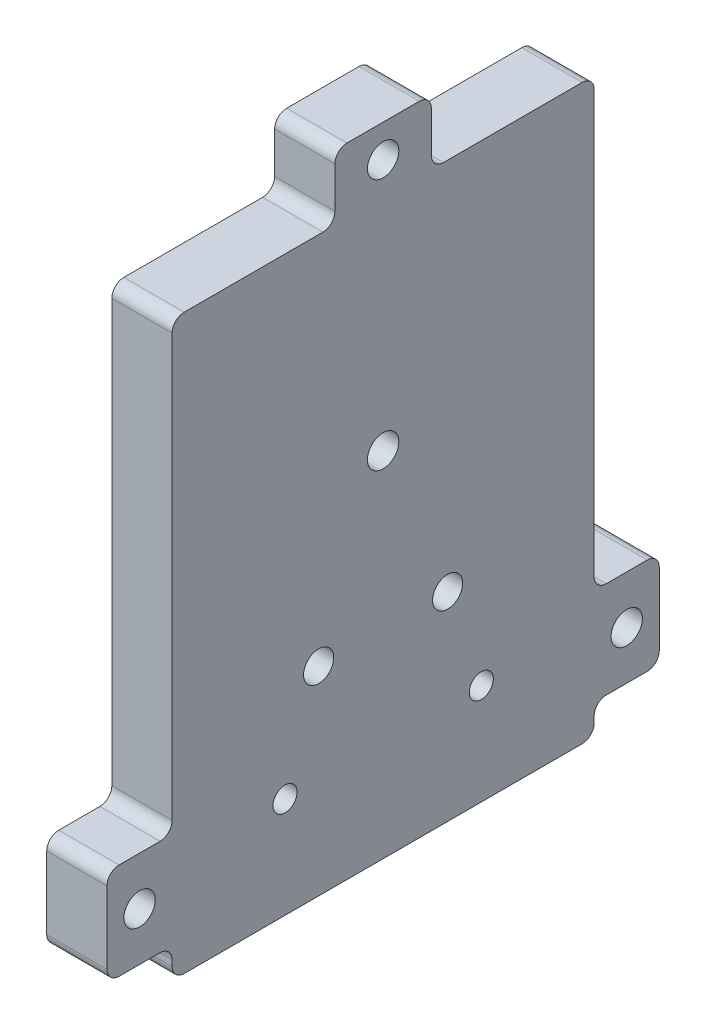
SolidWorks part; units mm, degrees
ref_plane "Front Plane" through (0, 0, 0) normal (0, 0, 1) x (1, 0, 0)
ref_plane "Top Plane" through (0, 0, 0) normal (0, 1, 0) x (1, 0, 0)
ref_plane "Right Plane" through (0, 0, 0) normal (1, 0, 0) x (0, 0, -1)
sketch "Sketch11" plane through (0, 0, 0) normal (1, 0, 0) x (0, 0, -1)
  line L0 (0, 0) -> (0, 16.256) construction
  line L1 (0, 0) -> (6.7945, 0) construction
  line L2 (0, 0) -> (10.3363, -10.3363) construction
  line L3 (0, -17.78) -> (0, 36.195) construction
  line L4 (-19.05, 36.195) -> (19.05, 36.195)
  line L5 (-19.05, 36.195) -> (-19.05, -17.78)
  line L6 (-19.05, -17.78) -> (19.05, -17.78)
  line L7 (19.05, 36.195) -> (19.05, -17.78)
  circle A5 centre (0, 16.256) radius 1.651
  circle A6 centre (6.7945, 0) radius 1.5875
  circle A7 centre (10.3363, -10.3363) radius 1.27
  circle A10 centre (-10.3363, -10.3363) radius 1.27
  circle A11 centre (-6.7945, 0) radius 1.5875
  dimension "D1" = 3.302
  dimension "D2" = 3.175
  dimension "D3" = 53.975
  dimension "D4" = 38.1
  dimension "D5" = 2.54
  dimension "D6" = 16.256
  dimension "D7" = 6.7945
  dimension "D8" = 10.3363
  dimension "D9" = 10.3363
  dimension "D10" = 17.78
extrude "Boss-Extrude1" add sketch "Sketch11" against normal blind 3.175
sketch "Sketch12" plane through (0, 0, 0) normal (1, 0, 0) x (0, 0, -1)
  line L0 (-22.225, 39.37) -> (-22.225, -20.955)
  line L1 (-22.225, -20.955) -> (22.225, -20.955)
  line L2 (22.225, -20.955) -> (22.225, 39.37)
  line L3 (22.225, 39.37) -> (-22.225, 39.37)
  line L4 (-19.05, 36.195) -> (-19.05, -17.78)
  line L5 (-19.05, -17.78) -> (19.05, -17.78)
  line L6 (19.05, -17.78) -> (19.05, 36.195)
  line L7 (19.05, 36.195) -> (-19.05, 36.195)
  line L8 (-19.05, 36.195) -> (-19.05, -17.78)
  line L9 (-19.05, -17.78) -> (19.05, -17.78)
  line L10 (19.05, -17.78) -> (19.05, 36.195)
  line L11 (19.05, 36.195) -> (-19.05, 36.195)
  dimension "D1" = 0
  dimension "D2" = 3.175
extrude "Boss-Extrude2" add sketch "Sketch12" against normal blind 6.35
sketch "Sketch13" plane through (0, 0, 0) normal (1, 0, 0) x (0, 0, -1)
  line L0 (22.225, 39.37) -> (-22.225, 39.37) construction
  line L1 (-22.225, -17.78) -> (-29.083, -17.78)
  line L2 (-22.225, -17.78) -> (-22.225, -7.62)
  line L3 (-22.225, -7.62) -> (-29.083, -7.62)
  line L4 (-29.083, -17.78) -> (-29.083, -7.62)
  line L5 (5.08, 39.37) -> (-5.08, 39.37)
  line L6 (5.08, 39.37) -> (5.08, 46.228)
  line L7 (5.08, 46.228) -> (-5.08, 46.228)
  line L8 (-5.08, 39.37) -> (-5.08, 46.228)
  line L9 (0, -20.955) -> (0, 39.37) construction
  line L10 (-22.225, -20.955) -> (22.225, -20.955) construction
  line L11 (-25.654, -17.78) -> (-25.654, -7.62) construction
  line L12 (-29.083, -12.7) -> (-22.225, -12.7) construction
  line L13 (-5.08, 42.799) -> (5.08, 42.799) construction
  line L14 (0, 46.228) -> (0, 39.37) construction
  line L15 (22.225, -7.62) -> (29.083, -7.62)
  line L16 (29.083, -17.78) -> (29.083, -7.62)
  line L17 (22.225, -17.78) -> (29.083, -17.78)
  line L18 (22.225, -17.78) -> (22.225, -7.62)
  line L19 (-19.05, -17.78) -> (19.05, -17.78) construction
  circle A0 centre (-25.654, -12.7) radius 1.651
  circle A1 centre (0, 42.799) radius 1.651
  circle A2 centre (25.654, -12.7) radius 1.651
  dimension "D5" = 3.302
  dimension "D6" = 3.302
  dimension "D1" = 10.16
  dimension "D2" = 6.858
  dimension "D3" = 10.16
  dimension "D4" = 6.858
extrude "Boss-Extrude3" add sketch "Sketch13" against normal up to surface (6.35 mm away) up to face at (-6.35, 9.2075, 0)
sketch "Sketch14" plane through (-3.175, 0, 0) normal (-1, 0, 0) x (0, 0, 1)
  circle A0 centre (-6.7945, 0) radius 1.5875 construction
  circle A1 centre (-6.7945, 0) radius 1.5875
  circle A2 centre (6.7945, 0) radius 1.5875 construction
  circle A3 centre (6.7945, 0) radius 1.5875
  circle A4 centre (10.3363, -10.3363) radius 1.27 construction
  circle A5 centre (-10.3363, -10.3363) radius 1.27 construction
  circle A6 centre (10.3363, -10.3363) radius 1.27
  circle A7 centre (-10.3363, -10.3363) radius 1.27
  circle A8 centre (-6.7945, 0) radius 3.6195
  circle A9 centre (6.7945, 0) radius 3.6195
  circle A10 centre (-10.3363, -10.3363) radius 3.302
  circle A11 centre (10.3363, -10.3363) radius 3.302
  dimension "D1" = 2.032
  dimension "D2" = 2.032
extrude "Boss-Extrude4" add sketch "Sketch14" along normal blind 10.16
fillet "Fillet2" radius 1.27 16 edges at (-3.175, 39.37, 22.225) (-3.175, 39.37, -22.225) (-3.175, -7.62, -29.083) (-3.175, -17.78, 29.083) (-3.175, -7.62, 29.083) (-3.175, 46.228, 5.08) (-3.175, 46.228, -5.08) (-3.175, 39.37, -5.08) (-3.175, 39.37, 5.08) (-3.175, -7.62, -22.225) (-3.175, -7.62, 22.225) (-3.175, -17.78, -29.083) (-3.175, -17.78, 22.225) (-3.175, -17.78, -22.225) (-3.175, -20.955, -22.225) (-3.175, -20.955, 22.225)
